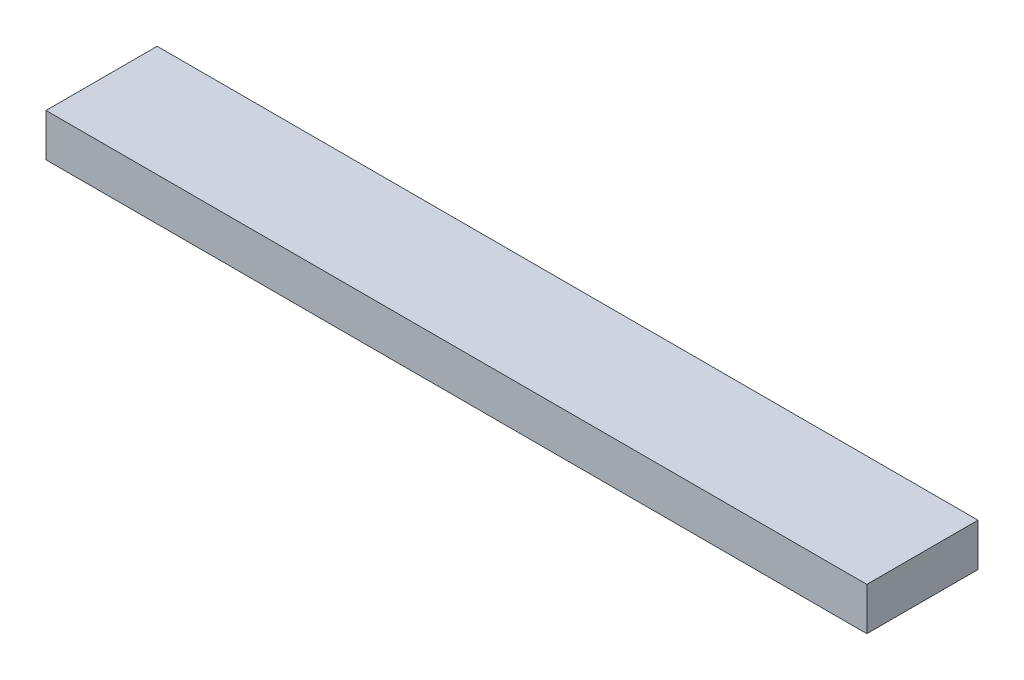
SolidWorks part; units mm, degrees
material "Free-Cutting Brass, UNS C36000"
ref_plane "Front Plane" through (0, 0, 0) normal (0, 0, 1) x (1, 0, 0)
ref_plane "Top Plane" through (0, 0, 0) normal (0, 1, 0) x (1, 0, 0)
ref_plane "Right Plane" through (0, 0, 0) normal (1, 0, 0) x (0, 0, -1)
sketch "Sketch1" plane through (0, 0, 0) normal (0, 1, 0) x (1, 0, 0)
  line L1 (0, 0) -> (60.96, 0)
  line L2 (0, 0) -> (0, 8.255)
  line L3 (0, 8.255) -> (60.96, 8.255)
  line L4 (60.96, 0) -> (60.96, 8.255)
  dimension "D1" = 60.96
  dimension "D2" = 8.255
extrude "Boss-Extrude1" add sketch "Sketch1" along normal blind 3.175
